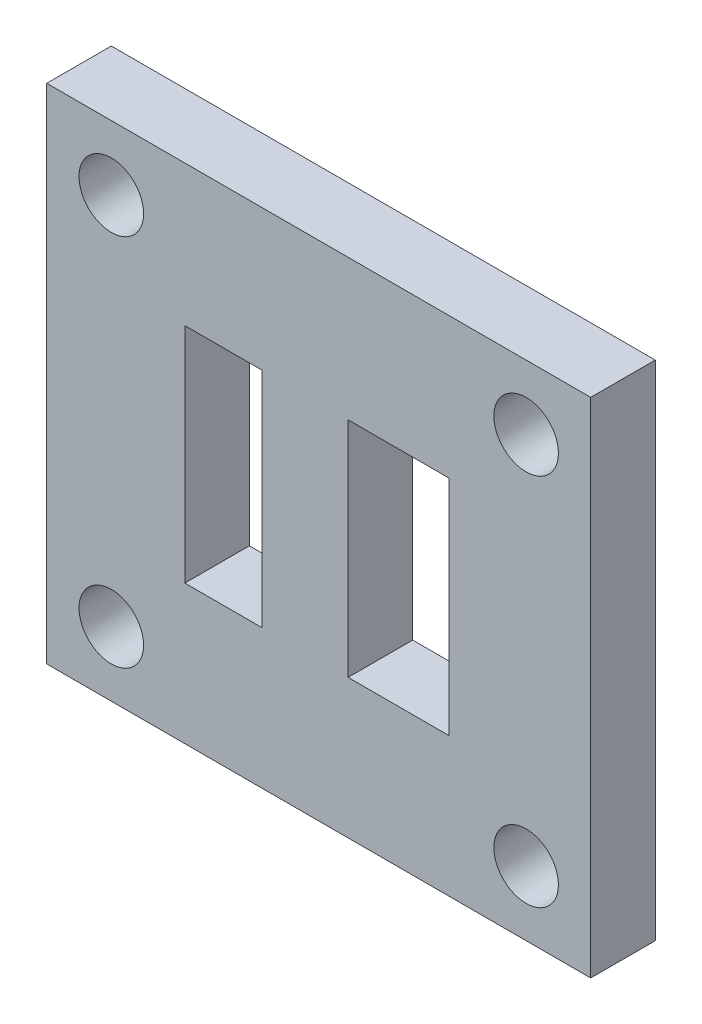
SolidWorks part; units mm, degrees
ref_plane "Front Plane" through (0, 0, 0) normal (0, 0, 1) x (1, 0, 0)
ref_plane "Top Plane" through (0, 0, 0) normal (0, 1, 0) x (1, 0, 0)
ref_plane "Right Plane" through (0, 0, 0) normal (1, 0, 0) x (0, 0, -1)
sketch "Sketch1" plane through (0, 0, 0) normal (0, 0, 1) x (1, 0, 0)
  line L0 (-2.635, 5.14) -> (-2.635, -5.22)
  line L1 (-12.635, 11.68) -> (12.635, 11.68)
  line L2 (-12.635, 11.68) -> (-12.635, -11.68)
  line L3 (-12.635, -11.68) -> (12.635, -11.68)
  line L4 (12.635, 11.68) -> (12.635, -11.68)
  line L5 (-12.635, 11.68) -> (12.635, -11.68) construction
  line L6 (-12.635, -11.68) -> (12.635, 11.68) construction
  line L7 (-6.22, 5.14) -> (6.05, 5.14)
  line L8 (-6.22, 5.14) -> (-6.22, -5.22)
  line L9 (-6.22, -5.22) -> (6.05, -5.22)
  line L10 (6.05, 5.14) -> (6.05, -5.22)
  line L11 (1.365, 5.14) -> (1.365, -5.22)
  circle A0 centre (9.635, 8.68) radius 1.5
  circle A1 centre (9.635, -8.68) radius 1.5
  circle A2 centre (-9.635, -8.68) radius 1.5
  circle A3 centre (-9.635, 8.68) radius 1.5
  point P0 (0, 0)
  dimension "D3" = 3
  dimension "D4" = 3
  dimension "D5" = 3
  dimension "D6" = 3
  dimension "D7" = 3
  dimension "D8" = 3
  dimension "D9" = 3
  dimension "D10" = 3
  dimension "D11" = 3
  dimension "D12" = 3
  dimension "D13" = 3
  dimension "D14" = 3
  dimension "D1" = 23.36
  dimension "D2" = 25.27
  dimension "D15" = 10.36
  dimension "D16" = 12.27
  dimension "D17" = 10
  dimension "D18" = 6.22
  dimension "D19" = 4
  dimension "D20" = 5.22
extrude "Boss-Extrude1" add sketch "Sketch1" along normal blind 3 contours L11 L7 L0 L9 | L4 L1 L2 L3 A3 A2 A1 A0 L7 L10 L9 L8
